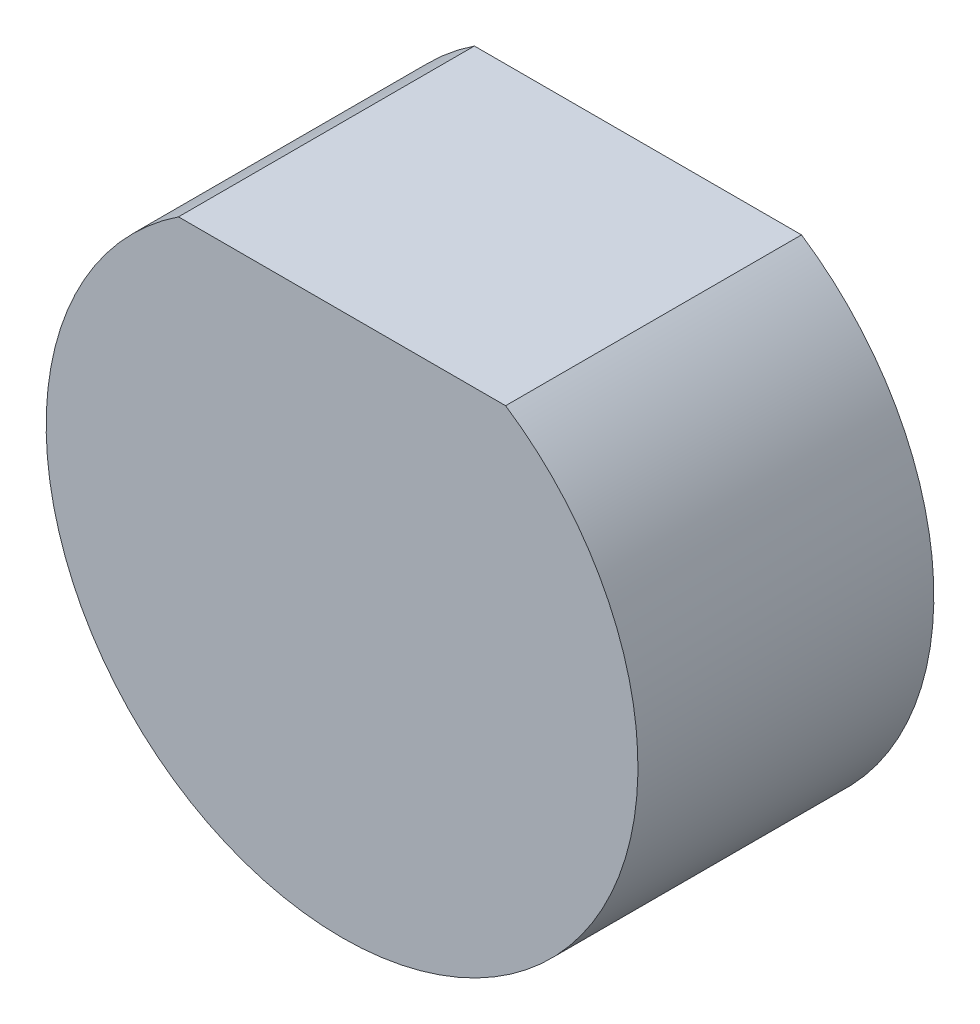
SolidWorks part; units mm, degrees
material "Acrylic (Medium-high impact)"
ref_plane "Front Plane" through (0, 0, 0) normal (0, 0, 1) x (1, 0, 0)
ref_plane "Top Plane" through (0, 0, 0) normal (0, 1, 0) x (1, 0, 0)
ref_plane "Right Plane" through (0, 0, 0) normal (1, 0, 0) x (0, 0, -1)
sketch "Sketch1" plane through (0, 0, 0) normal (0, 0, 1) x (1, 0, 0)
  line L0 (-3.3166, 5) -> (3.3166, 5)
  arc A0 (-3.3166, 5) -> (3.3166, 5) centre (0, 0) ccw
  dimension "D1" = 12
  dimension "D2" = 5
extrude "Boss-Extrude1" add sketch "Sketch1" along normal blind 6
sketch "Sketch2" plane through (0, 0, 6) normal (0, 0, 1) x (1, 0, 0)
  circle A0 centre (0, 0) radius 3 construction
  circle A1 centre (0, 0) radius 2.5 construction
  dimension "D1" = 6
  dimension "D2" = 5
